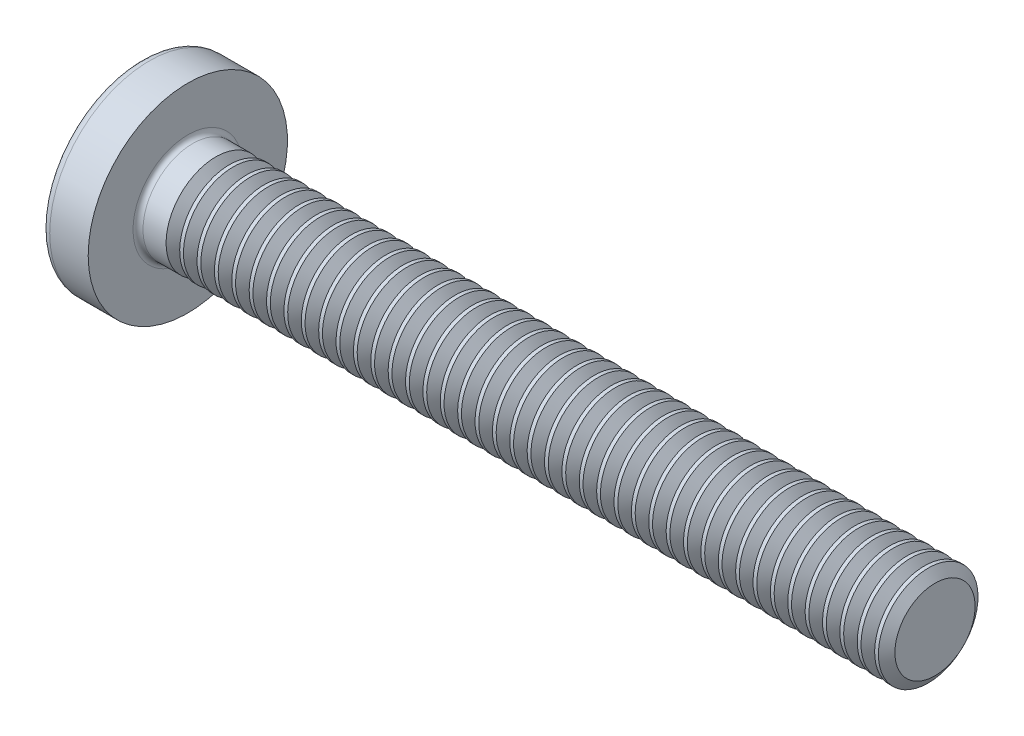
SolidWorks part; units mm, degrees
ref_plane "Plane1" through (0, 0, 0) normal (0, 0, 1) x (1, 0, 0)
ref_plane "Plane2" through (0, 0, 0) normal (0, 1, 0) x (1, 0, 0)
ref_plane "Plane3" through (0, 0, 0) normal (1, 0, 0) x (0, 0, -1)
sketch "BodySke" plane through (0, 0, 0) normal (0, 0, 1) x (1, 0, 0)
  line L0 (3.1, 2) -> (3.1, 4)
  line L1 (3.45, 6.35) -> (3.45, -3.175) construction
  line L2 (-25.4, 0) -> (127, 0) construction
  line L3 (33.1, 0) -> (0, 0)
  line L4 (3.1, 2) -> (33.1, 2)
  line L5 (33.1, 2) -> (33.1, 0)
  line L6 (1.5553, 4) -> (3.1, 4)
  line L8 (3.1, 6.35) -> (3.1, -3.175) construction
  arc A0 (1.2654, 3.8534) -> (0, 0) centre (6.5, 0) ccw
  arc A2 (1.2654, 3.8534) -> (1.5553, 4) centre (1.5553, 3.64) cw
  dimension "Head_crown_rad" = 6.5
  dimension "Head_fillet_rad" = 0.36
  dimension "Length" = 30
  dimension "Head_ht" = 3.1
  dimension "Head_dia" = 8
  dimension "Advance" = 0.7
  dimension "Thread_nom" = 30
  dimension "Diameter" = 4
revolve "Base-Revolve" add sketch "BodySke"
cosmetic thread "ThreadCosmetic" [suppressed]
fillet "Fillet1" radius 0.2 1 edges at (3.1, 0, 2)
sketch "Sketch3" plane through (0, 0, 0) normal (1, 0, 0) x (0, 0, -1)
  line L0 (0.515, -2.15) -> (-0.515, -2.15)
  line L1 (0.515, -2.15) -> (0.515, 2.15)
  line L2 (-0.515, 2.15) -> (0.515, 2.15)
  line L3 (-0.515, 2.15) -> (-0.515, -2.15)
  dimension "Cross_dia" = 4.3
  dimension "D1" = 2.15
  dimension "Cross_width" = 1.03
  dimension "D2" = 0.515
ref_plane "Plane4" through (2.34, 0, 0) normal (1, 0, 0) x (0, 0, -1)
sketch "Sketch4" plane through (2.34, 0, 0) normal (1, 0, 0) x (0, 0, -1)
  line L0 (0.515, -0.9833) -> (-0.515, -0.9833)
  line L1 (0.515, -0.9833) -> (0.515, 0.9833)
  line L2 (-0.515, 0.9833) -> (0.515, 0.9833)
  line L3 (-0.515, 0.9833) -> (-0.515, -0.9833)
  dimension "D1" = 1.03
  dimension "D2" = 1.9666
  dimension "D3" = 0.515
  dimension "D4" = 0.9833
loft "Recess" cut profiles "Sketch3", "Sketch4"
pattern_circular "RecPat" count 2 every 90 about axis through (0, 0, 0) along (1, 0, 0) of "Recess"
sketch "RecCorSke" plane through (0, 0, 0) normal (0, 0, 1) x (1, 0, 0)
  line L0 (-3.175, 0) -> (15.875, 0) construction
  line L1 (-25.4, 0) -> (127, 0) construction
  line L2 (0, 0) -> (0, 1.0146)
  line L3 (0, 1.0146) -> (2.34, 0.851)
  line L4 (2.34, 0.851) -> (2.6165, 0)
  line L5 (2.6165, 0) -> (0, 0)
  dimension "Diameter" = 1.702
  dimension "Depth" = 2.34
  dimension "Draft_angle" = 4
  dimension "Bottom_angle" = 18
revolve "RecessCore" cut sketch "RecCorSke" angle 360 about L0
sketch "ThdSchSke" plane through (0, 0, 0) normal (0, 0, 1) x (1, 0, 0)
  line L0 (4.5, -1.61) -> (4.2269, -2)
  line L1 (4.5, -1.61) -> (4.7731, -2)
  line L2 (4.7731, -2) -> (4.7731, -2.5)
  line L3 (-3.175, 0) -> (5.1513, 0) construction
  line L5 (4.7731, -2.5) -> (4.2269, -2.5)
  line L6 (4.2269, -2.5) -> (4.2269, -2)
  dimension "Diameter" = 4
  dimension "SideAngle" = 55
  dimension "VeeAngle" = 70
  dimension "Thread_minor" = 3.22
  dimension "Overcut" = 5
  dimension "Start" = 4.5
revolve "ThreadSchematic" cut sketch "ThdSchSke" angle 360 about L3
pattern_linear "ThdSchPat" count 42 spacing 0.6976 along (1, 0, 0) of "ThreadSchematic"
equation "\"D1@Sketch3\" = \"Cross_dia@Sketch3\" / 2"
equation "\"D2@Sketch3\" = \"Cross_width@Sketch3\" / 2"
equation "\"Depth@RecCorSke\" = \"Cross_depth@Plane4\""
equation "\"D1@Sketch4\" = \"Cross_width@Sketch3\""
equation "\"D2@Sketch4\" = \"Cross_dia@Sketch3\" - 2.0 * \"Cross_depth@Plane4\" * tan(26.5  * 0.017453292)"
equation "\"D3@Sketch4\" = \"D1@Sketch4\" / 2"
equation "\"D4@Sketch4\" = \"D2@Sketch4\" / 2"
equation "\"Thread_length@ThreadCosmetic\" = ((sgn( (\"Length@BodySke\" - \"Advance@BodySke\" * 2.0 ) - \"Thread_nom@BodySke\" )-1)*( (\"Length@BodySke\" - \"Advance@BodySke\" * 2.0 ) - \"Thread_nom@BodySke\" ))/-2+ \"Thread_nom@BodySke\""
equation "\"Thread_minor@ThdSchSke\" = \"Thread_minor@ThreadCosmetic\""
equation "\"Diameter@ThdSchSke\" = \"Diameter@BodySke\""
equation "\"Overcut@ThdSchSke\" = \"Diameter@BodySke\" * 1.25"
equation "\"Start@ThdSchSke\" = \"Head_ht@BodySke\" + \"Length@BodySke\" - \"Thread_length@ThreadCosmetic\"  '---Non-countersunk---"
equation "\"Num_threads@ThdSchPat\" = int( \"Thread_length@ThreadCosmetic\" / \"Advance@BodySke\" + 0.999 )  + 1"
equation "\"Advance@ThdSchPat\" = \"Thread_length@ThreadCosmetic\" /  (\"Num_threads@ThdSchPat\" - 1) 'relax it"
